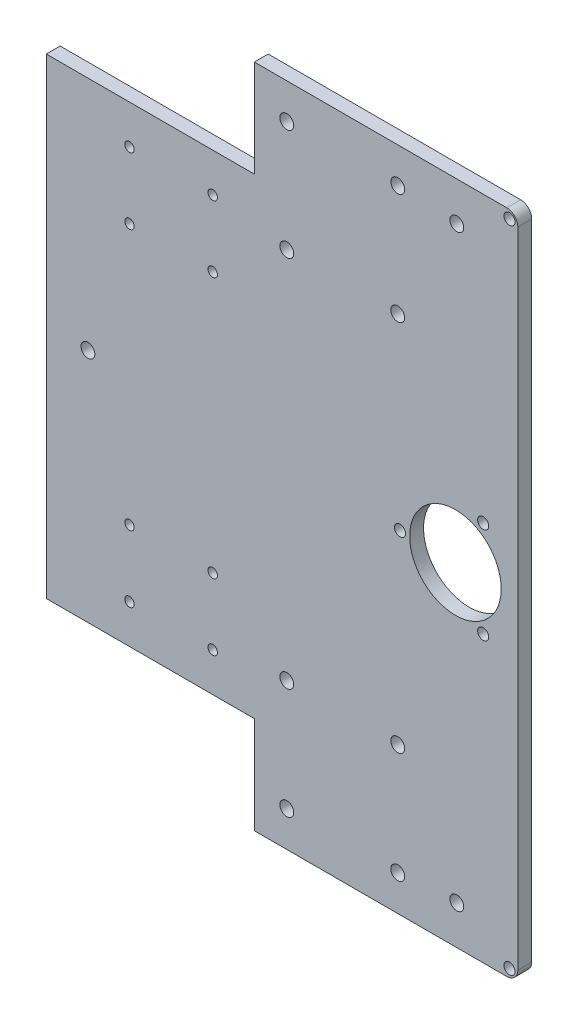
SolidWorks part; units mm, degrees
ref_plane "Front Plane" through (0, 0, 0) normal (0, 0, 1) x (1, 0, 0)
ref_plane "Top Plane" through (0, 0, 0) normal (0, 1, 0) x (1, 0, 0)
ref_plane "Right Plane" through (0, 0, 0) normal (1, 0, 0) x (0, 0, -1)
sketch "Sketch1" plane through (0, 0, 0) normal (0, 0, 1) x (1, 0, 0)
  line L1 (-85, 120) -> (85, 120)
  line L2 (-85, 120) -> (-85, -120)
  line L3 (-85, -120) -> (85, -120)
  line L4 (85, 120) -> (85, -120)
  line L5 (-85, 120) -> (85, -120) construction
  line L6 (-85, -120) -> (85, 120) construction
  point P0 (0, 0)
  dimension "D1" = 240
  dimension "D2" = 170
extrude "Boss-Extrude1" add sketch "Sketch1" along normal blind 5
sketch "Sketch2" plane through (0, 0, 5) normal (0, 0, 1) x (1, 0, 0)
  circle A0 centre (62.5, 0) radius 16.5
  dimension "D1" = 33
extrude "Cut-Extrude1" cut sketch "Sketch2" against normal through all
sketch "Sketch3" plane through (0, 0, 5) normal (0, 0, 1) x (1, 0, 0)
  circle A0 centre (72.5, -17.3205) radius 2
  circle A1 centre (72.5, 17.3205) radius 2
  circle A2 centre (42.5, 0) radius 2
extrude "Cut-Extrude2" cut sketch "Sketch3" against normal through all
sketch "Sketch4" plane through (0, 0, 5) normal (0, 0, 1) x (1, 0, 0)
  line L0 (2.75, 0) -> (-2.75, 0) construction
  circle A0 centre (-25, 47) radius 1.7
  circle A1 centre (-25, 71) radius 1.7
  circle A2 centre (-55, 47) radius 1.7
  circle A3 centre (-55, 71) radius 1.7
  circle A4 centre (-55, -71) radius 1.7
  circle A5 centre (-25, -71) radius 1.7
  circle A6 centre (-55, -47) radius 1.7
  circle A7 centre (-25, -47) radius 1.7
extrude "Cut-Extrude3" cut sketch "Sketch4" against normal through all
sketch "Sketch5" plane through (0, 0, 5) normal (0, 0, 1) x (1, 0, 0)
  line L0 (85, 120) -> (-85, 120) construction
  line L1 (-10, 120) -> (-85, 120)
  line L2 (-10, 120) -> (-10, 85)
  line L3 (-10, 85) -> (-85, 85)
  line L4 (-85, 120) -> (-85, 85)
  line L5 (-85, 120) -> (-85, -120) construction
  line L6 (2.75, 0) -> (-2.75, 0) construction
  line L7 (-10, -120) -> (-85, -120)
  line L8 (-85, -120) -> (-85, -85)
  line L9 (-10, -85) -> (-85, -85)
  line L10 (-10, -120) -> (-10, -85)
  dimension "D1" = 75
  dimension "D2" = 35
extrude "Cut-Extrude4" cut sketch "Sketch5" against normal through all
fillet "Fillet1" radius 4 1 edges at (85, -120, 2.5)
sketch "Sketch6" plane through (0, 0, 5) normal (0, 0, 1) x (1, 0, 0)
  circle A0 centre (82, -117) radius 2
  dimension "D1" = 4
extrude "Cut-Extrude5" cut sketch "Sketch6" against normal through all
mirror "Mirror5" about plane through (0, 0, 0) normal (0, 1, 0) of "Cut-Extrude5"
fillet "Fillet2" radius 4 1 edges at (85, 120, 2.5)
fillet "Fillet3" [suppressed] radius 4
sketch "Sketch7" plane through (0, 0, 5) normal (0, 0, 1) x (1, 0, 0)
  circle A0 centre (41.7, 107.25) radius 2.5
  circle A1 centre (41.7, 67.25) radius 2.5
  circle A2 centre (1.7, 67.25) radius 2.5
  circle A3 centre (1.7, 107.25) radius 2.5
  circle A4 centre (41.7, -107.25) radius 2.5
  circle A5 centre (1.7, -107.25) radius 2.5
  circle A6 centre (1.7, -67.25) radius 2.5
  circle A7 centre (41.7, -67.25) radius 2.5
  dimension "D1" = 5
extrude "Cut-Extrude6" cut sketch "Sketch7" against normal through all
sketch "Sketch8" plane through (0, 0, 0) normal (0, 0, -1) x (-1, 0, 0)
  circle A0 centre (-63, 106) radius 2.5
  circle A1 centre (-63, -106) radius 2.5
  circle A2 centre (70, 0) radius 2.5
  dimension "D1" = 5
extrude "Cut-Extrude7" cut sketch "Sketch8" against normal through all
